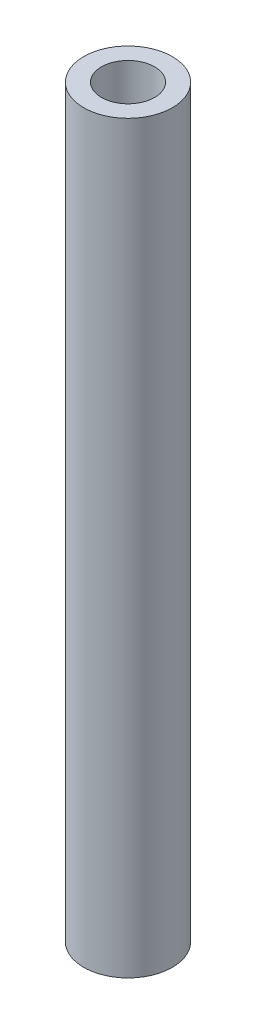
SolidWorks part; units mm, degrees
material "6061 合金"
ref_plane "前视基准面" through (0, 0, 0) normal (0, 0, 1) x (1, 0, 0)
ref_plane "上视基准面" through (0, 0, 0) normal (0, 1, 0) x (1, 0, 0)
ref_plane "右视基准面" through (0, 0, 0) normal (1, 0, 0) x (0, 0, -1)
sketch "草图1" plane through (0, 0, 0) normal (0, 1, 0) x (1, 0, 0)
  circle A0 centre (0, 0) radius 1.5
  circle A1 centre (0, 0) radius 2.5
  dimension "D1" = 3
  dimension "D2" = 5
extrude "凸台-拉伸1" add sketch "草图1" along normal blind 42
